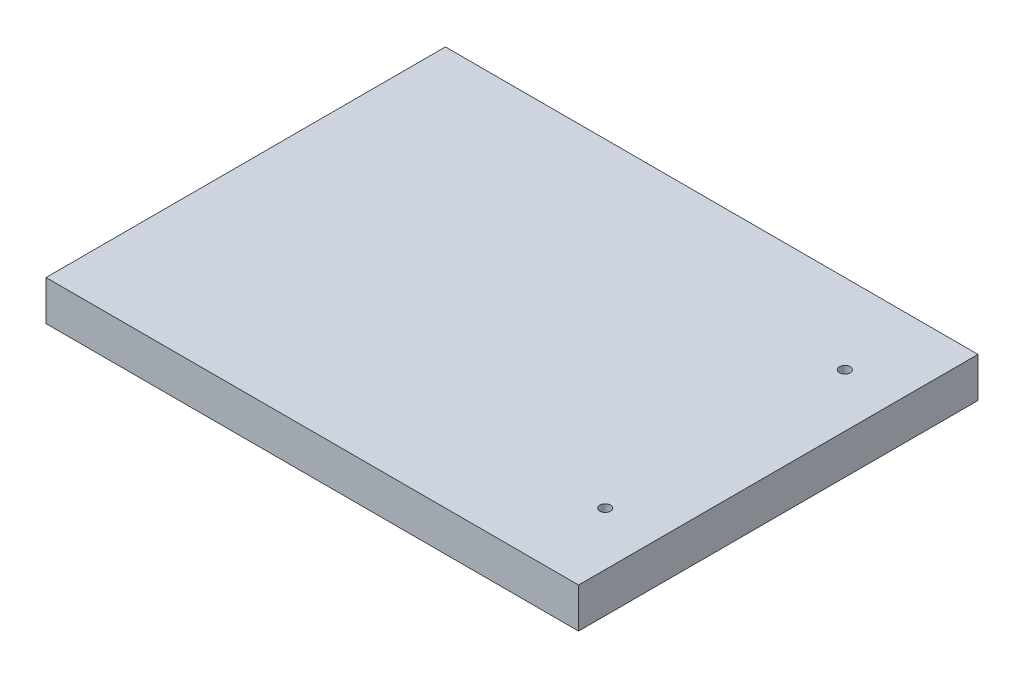
SolidWorks part; units mm, degrees
ref_plane "Front Plane" through (0, 0, 0) normal (0, 0, 1) x (1, 0, 0)
ref_plane "Top Plane" through (0, 0, 0) normal (0, 1, 0) x (1, 0, 0)
ref_plane "Right Plane" through (0, 0, 0) normal (1, 0, 0) x (0, 0, -1)
sketch "Sketch1" plane through (0, 0, 0) normal (0, 1, 0) x (1, 0, 0)
  line L1 (0, 0) -> (200, 0)
  line L2 (0, 0) -> (0, 150)
  line L3 (0, 150) -> (200, 150)
  line L4 (200, 0) -> (200, 150)
  dimension "D1" = 150
  dimension "200" = 200
extrude "Boss-Extrude1" add sketch "Sketch1" along normal blind 15
sketch "Sketch2" plane through (0, 15, 0) normal (0, 1, 0) x (1, 0, 0)
  line L0 (200, 150) -> (0, 150) construction
  line L1 (200, 0) -> (200, 150) construction
  line L2 (0, 0) -> (200, 0) construction
  circle A0 centre (180, 120) radius 10
  circle A1 centre (180, 30) radius 10
  point P0 (180, 120)
  point P2 (180, 30)
  dimension "D1" = 20
  dimension "D2" = 20
  dimension "D3" = 30
  dimension "D4" = 20
  dimension "D5" = 20
  dimension "D6" = 30
hole_wizard "Ø4.0 (4) Diameter Hole3" positions "Sketch2" profile "Sketch3" hole size "Ø4.0" standard "ANSI Metric"
sketch "Sketch3" plane through (180, 15, -120) normal (1, 0, 0) x (0, 0, 1)
  line L0 (0, 0) -> (0, 6.7017)
  line L1 (0, 6.7017) -> (2, 5.5)
  line L2 (2, 5.5) -> (2, 0)
  line L5 (2, 0) -> (0, 0)
  line L10 (0, 6.7017) -> (-2, 5.5) construction
  line L11 (0, -6.35) -> (0, 107.95) construction
  dimension "Hole Dia." = 4
  dimension "Hole Depth" = 5.5
  dimension "Drill Angle" = 118
